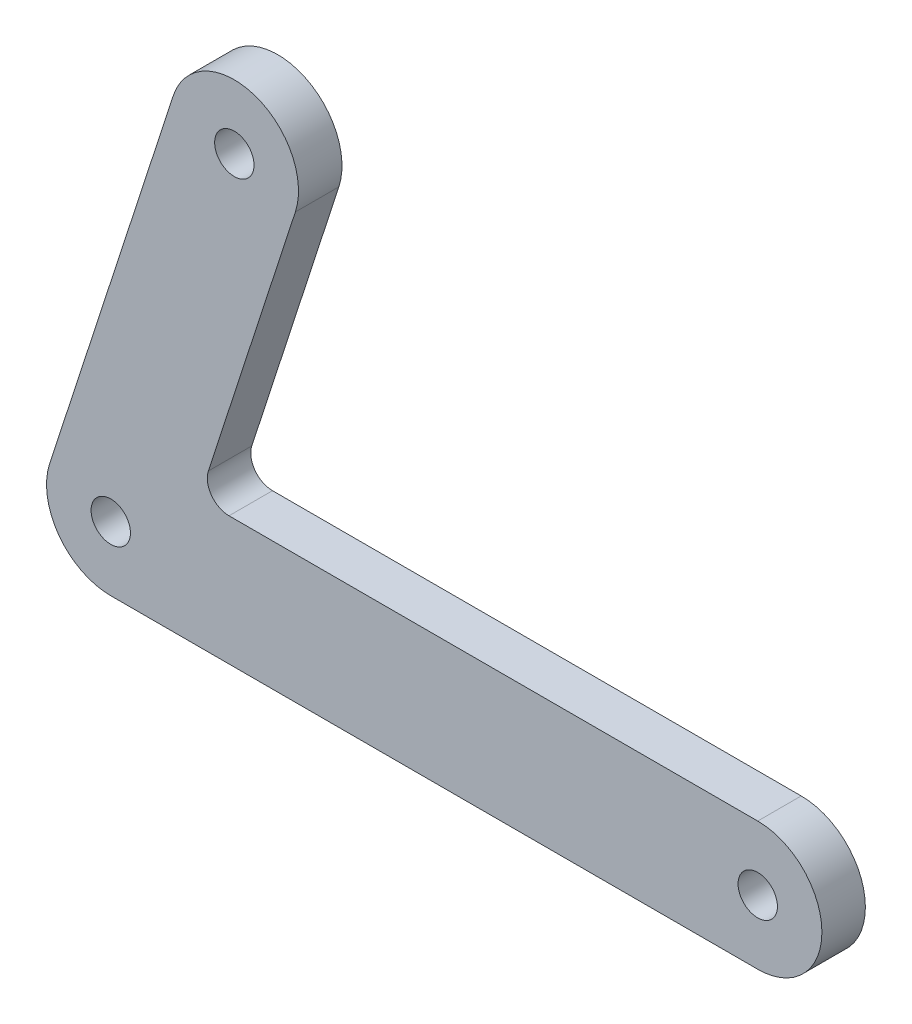
SolidWorks part; units mm, degrees
ref_plane "Front Plane" through (0, 0, 0) normal (0, 0, 1) x (1, 0, 0)
ref_plane "Top Plane" through (0, 0, 0) normal (0, 1, 0) x (1, 0, 0)
ref_plane "Right Plane" through (0, 0, 0) normal (1, 0, 0) x (0, 0, -1)
sketch "Sketch1" plane through (0, 0, 0) normal (0, 0, 1) x (1, 0, 0)
  line L0 (57.9856, 90.3788) -> (133.5856, 90.3788)
  line L1 (133.5856, 105.3788) -> (71.8045, 105.3788)
  line L2 (69.3888, 108.7037) -> (79.5568, 139.9978)
  line L3 (65.291, 144.633) -> (50.8527, 100.1965)
  arc A5 (55.6856, 97.8788) -> (60.2856, 97.8788) centre (57.9856, 97.8788) ccw
  arc A9 (60.2856, 97.8788) -> (55.6856, 97.8788) centre (57.9856, 97.8788) ccw
  arc A10 (50.8527, 100.1965) -> (57.9856, 90.3788) centre (57.9856, 97.8788) ccw
  arc A11 (133.5856, 90.3788) -> (141.0856, 97.8788) centre (133.5856, 97.8788) ccw
  arc A24 (141.0856, 97.8788) -> (133.5856, 105.3788) centre (133.5856, 97.8788) ccw
  arc A25 (50.8527, 100.1965) -> (57.9856, 90.3788) centre (57.9856, 97.8788) ccw
  arc A26 (79.5568, 139.9978) -> (65.291, 144.633) centre (72.4239, 142.3154) ccw
  arc A27 (131.2856, 97.8788) -> (135.8856, 97.8788) centre (133.5856, 97.8788) ccw
  arc A28 (135.8856, 97.8788) -> (131.2856, 97.8788) centre (133.5856, 97.8788) ccw
  arc A29 (70.2365, 143.0261) -> (74.6113, 141.6047) centre (72.4239, 142.3154) ccw
  arc A30 (74.6113, 141.6047) -> (70.2365, 143.0261) centre (72.4239, 142.3154) ccw
  arc A31 (71.8045, 105.3788) -> (69.3888, 108.7037) centre (71.8045, 107.9188) cw
  dimension "D1" = 2.54
extrude "Boss-Extrude1" add sketch "Sketch1" along normal blind 5.08
